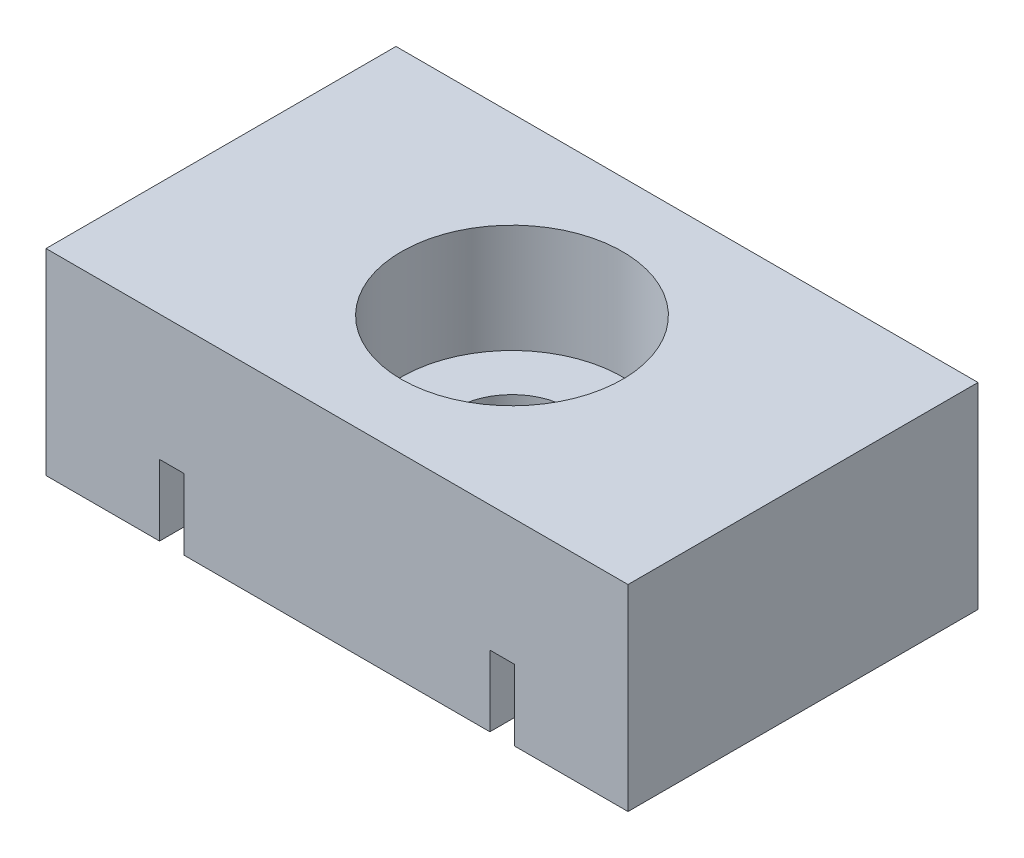
SolidWorks part; units mm, degrees
material "Nylon 6/10"
ref_plane "Front Plane" through (0, 0, 0) normal (0, 0, 1) x (1, 0, 0)
ref_plane "Top Plane" through (0, 0, 0) normal (0, 1, 0) x (1, 0, 0)
ref_plane "Right Plane" through (0, 0, 0) normal (1, 0, 0) x (0, 0, -1)
sketch "Sketch1" plane through (0, 0, 0) normal (0, 1, 0) x (1, 0, 0)
  line L1 (-9.398, -5.6515) -> (9.398, -5.6515)
  line L2 (-9.398, -5.6515) -> (-9.398, 5.6515)
  line L3 (-9.398, 5.6515) -> (9.398, 5.6515)
  line L4 (9.398, -5.6515) -> (9.398, 5.6515)
  line L5 (-9.398, -5.6515) -> (9.398, 5.6515) construction
  line L6 (-9.398, 5.6515) -> (9.398, -5.6515) construction
  point P0 (0, 0)
  dimension "D1" = 18.796
  dimension "D2" = 11.303
extrude "Base" add sketch "Sketch1" along normal blind 6.35
sketch "Sketch2" plane through (0, 0, 0) normal (0, -1, 0) x (1, 0, 0)
  line L0 (-5.334, 5.6515) -> (-5.334, 4.1783) construction
  line L1 (-9.398, 5.6515) -> (9.398, 5.6515) construction
  line L2 (-4.9371, 5.6515) -> (-4.9371, 4.1783)
  line L3 (-5.7309, 5.6515) -> (-5.7309, 4.1783)
  line L4 (5.334, 5.6515) -> (5.334, 4.1783) construction
  line L5 (5.7309, 5.6515) -> (5.7309, 4.1783)
  line L6 (4.9371, 5.6515) -> (4.9371, 4.1783)
  line L7 (0, 0) -> (0, 225.9023) construction
  arc A0 (-4.9371, 5.6515) -> (-5.7309, 5.6515) centre (-5.334, 5.6515) ccw
  arc A1 (-5.7309, 4.1783) -> (-4.9371, 4.1783) centre (-5.334, 4.1783) ccw
  arc A2 (5.7309, 5.6515) -> (4.9371, 5.6515) centre (5.334, 5.6515) ccw
  arc A3 (4.9371, 4.1783) -> (5.7309, 4.1783) centre (5.334, 4.1783) ccw
  point P4 (-5.334, 4.9149)
  point P9 (5.334, 4.9149)
  dimension "D1" = 0.7937
  dimension "D2" = 10.668
  dimension "D3" = 1.4732
extrude "BoxSlots" cut sketch "Sketch2" against normal blind 2.286
hole_wizard "MoutingHole" positions "Sketch6" profile "Sketch5" counterbore size "#6" standard "ANSI Inch" end condition through all
sketch "Sketch6" plane through (0, 6.35, 0) normal (0, 1, 0) x (1, 0, 0)
  point P0 (0, 0)
sketch "Sketch5" plane through (0, 6.35, 0) normal (1, 0, 0) x (0, 0, 1)
  line L0 (0, 0) -> (0, 6.35)
  line L1 (0, 6.35) -> (1.8288, 6.35)
  line L3 (1.8288, 6.35) -> (1.8288, 3.5052)
  line L4 (1.8288, 3.5052) -> (3.5725, 3.5052)
  line L5 (3.5725, 3.5052) -> (3.5725, 0)
  line L7 (3.5725, 0) -> (0, 0)
  line L11 (0, -6.35) -> (0, 107.95) construction
  dimension "Thru Hole Dia." = 3.6576
  dimension "Thru Hole Depth" = 6.35
  dimension "C'Bore Dia." = 7.145
  dimension "C'Bore Depth" = 3.5052
